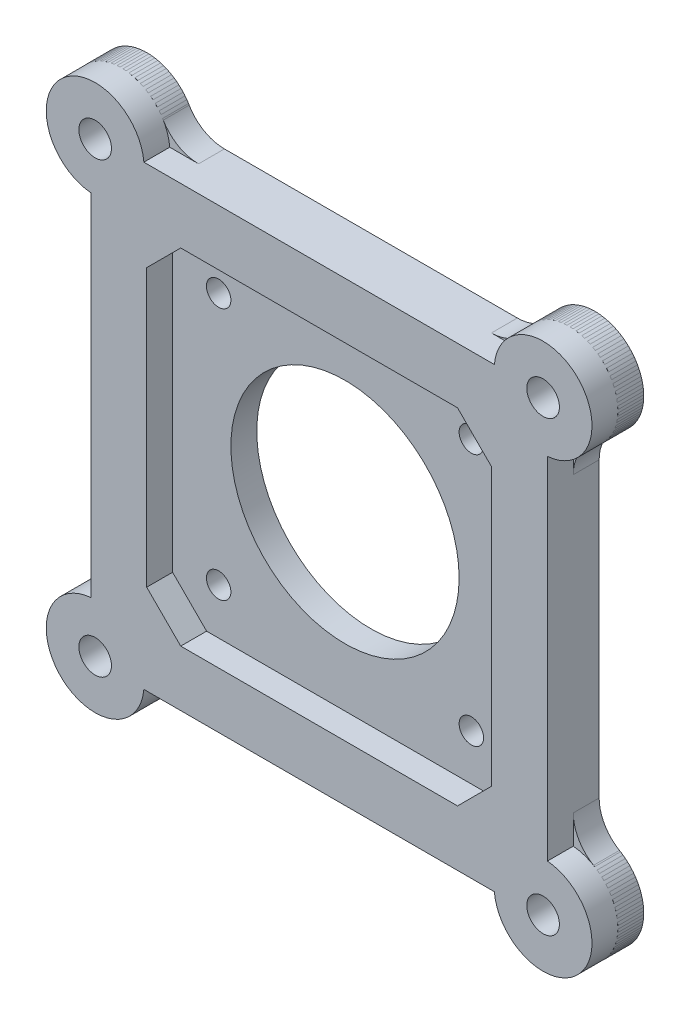
SolidWorks part; units mm, degrees
ref_plane "Plan de face" through (0, 0, 0) normal (0, 0, 1) x (1, 0, 0)
ref_plane "Plan de dessus" through (0, 0, 0) normal (0, 1, 0) x (1, 0, 0)
ref_plane "Plan de droite" through (0, 0, 0) normal (1, 0, 0) x (0, 0, -1)
sketch "Esquisse28" plane through (0, 0, 0) normal (0, 0, 1) x (1, 0, 0)
  line L0 (-21.5, -28.0054) -> (-28.0054, -21.5)
  line L1 (21.5, -28.0054) -> (-21.5, -28.0054)
  line L4 (28.0054, -21.5) -> (21.5, -28.0054)
  line L5 (28.0054, 21.5) -> (28.0054, -21.5)
  line L8 (21.5, 28.0054) -> (28.0054, 21.5)
  line L9 (-21.5, 28.0054) -> (21.5, 28.0054)
  line L10 (-28.0054, 21.5) -> (-21.5, 28.0054)
  line L11 (-28.0054, -21.5) -> (-28.0054, 21.5)
  line L16 (-16.9781, -21.15) -> (-21.15, -16.9781)
  line L17 (16.9781, -21.15) -> (-16.9781, -21.15)
  line L18 (21.15, -16.9781) -> (16.9781, -21.15)
  line L19 (21.15, 16.9781) -> (21.15, -16.9781)
  line L20 (16.9781, 21.15) -> (21.15, 16.9781)
  line L21 (-16.9781, 21.15) -> (16.9781, 21.15)
  line L22 (-21.15, 16.9781) -> (-16.9781, 21.15)
  line L23 (-21.15, -16.9781) -> (-21.15, 16.9781)
  point P1 (0, -21.15)
  point P2 (0, -28.0054)
  point P3 (28.0054, 0)
  point P24 (21.15, 0)
  dimension "D1" = 42.3
  dimension "D2" = 5.9
  dimension "D3" = 135
  dimension "D4" = 135
  dimension "D5" = 43
  dimension "D6" = 9.2
  dimension "D7" = 135
  dimension "D8" = 135
extrude "Boss.-Extru.2" add sketch "Esquisse28" along normal blind 6.35
sketch "Esquisse29" plane through (0, 0, 0) normal (0, 0, 1) x (1, 0, 0)
  line L0 (-46.0327, -46.0327) -> (46.0327, 46.0327) construction
  line L1 (-59.4617, 0) -> (59.4617, 0) construction
  circle A0 centre (27.4767, 27.4767) radius 6
  point P4 (0, 0)
  point P8 (0, 0)
  dimension "D2" = 12
  dimension "D1" = 45
extrude "Boss.-Extru.3" add sketch "Esquisse29" along normal up to surface (6.35 mm away) up to face at (0, 0, 6.35)
mirror "Symétrie1" about plane through (0, 0, 0) normal (1, 0, 0) of "Boss.-Extru.3"
mirror "Symétrie2" about plane through (0, 0, 0) normal (0, 1, 0) of "Symétrie1", "Boss.-Extru.3"
sketch "Esquisse30" plane through (0, 0, 6.35) normal (0, 0, 1) x (1, 0, 0)
  circle A0 centre (-27.4767, 27.4767) radius 2
  circle A1 centre (27.4767, 27.4767) radius 2
  circle A2 centre (27.4767, -27.4767) radius 2
  circle A3 centre (-27.4767, -27.4767) radius 2
  arc A4 (-28.0054, -21.5) -> (-21.5, -28.0054) centre (-27.4767, -27.4767) ccw construction
  arc A5 (-21.5, 28.0054) -> (-28.0054, 21.5) centre (-27.4767, 27.4767) ccw construction
  arc A6 (28.0054, 21.5) -> (21.5, 28.0054) centre (27.4767, 27.4767) ccw construction
  arc A7 (21.5, -28.0054) -> (28.0054, -21.5) centre (27.4767, -27.4767) ccw construction
  dimension "D1" = 4
extrude "Enlèv. mat.-Extru.1" cut sketch "Esquisse30" against normal through all
sketch "Esquisse31" plane through (0, 0, 0) normal (0, 0, 1) x (1, 0, 0)
  line L0 (-21.5, -28.0054) -> (21.5, -28.0054) construction
  line L1 (28.0054, -21.5) -> (28.0054, 21.5) construction
  line L2 (21.5, 28.0054) -> (-21.5, 28.0054) construction
  line L3 (-28.0054, 21.5) -> (-28.0054, -21.5) construction
  line L4 (-21.5, -28.0054) -> (21.5, -28.0054)
  line L5 (28.0054, -21.5) -> (28.0054, 21.5)
  line L6 (21.5, 28.0054) -> (-21.5, 28.0054)
  line L7 (-28.0054, 21.5) -> (-28.0054, -21.5)
  circle A0 centre (27.4767, 27.4767) radius 2 construction
  circle A1 centre (-27.4767, 27.4767) radius 2 construction
  circle A2 centre (-27.4767, -27.4767) radius 2 construction
  circle A3 centre (27.4767, -27.4767) radius 2 construction
  arc A4 (-28.0054, -21.5) -> (-21.5, -28.0054) centre (-27.4767, -27.4767) ccw construction
  arc A5 (21.5, -28.0054) -> (28.0054, -21.5) centre (27.4767, -27.4767) ccw construction
  arc A6 (28.0054, 21.5) -> (21.5, 28.0054) centre (27.4767, 27.4767) ccw construction
  arc A7 (-21.5, 28.0054) -> (-28.0054, 21.5) centre (-27.4767, 27.4767) ccw construction
  circle A8 centre (27.4767, 27.4767) radius 2
  circle A9 centre (-27.4767, 27.4767) radius 2
  circle A10 centre (-27.4767, -27.4767) radius 2
  circle A11 centre (27.4767, -27.4767) radius 2
  arc A12 (-28.0054, -21.5) -> (-21.5, -28.0054) centre (-27.4767, -27.4767) ccw
  arc A13 (21.5, -28.0054) -> (28.0054, -21.5) centre (27.4767, -27.4767) ccw
  arc A14 (28.0054, 21.5) -> (21.5, 28.0054) centre (27.4767, 27.4767) ccw
  arc A15 (-21.5, 28.0054) -> (-28.0054, 21.5) centre (-27.4767, 27.4767) ccw
extrude "Boss.-Extru.4" add sketch "Esquisse31" along normal blind 3.175 separate body
sketch "Esquisse32" plane through (0, 0, 3.175) normal (0, 0, 1) x (1, 0, 0)
  circle A0 centre (-15.5, -15.5) radius 1.5
  circle A1 centre (15.5, -15.5) radius 1.5
  circle A2 centre (15.5, 15.5) radius 1.5
  circle A3 centre (-15.5, 15.5) radius 1.5
  circle A4 centre (0, 0) radius 14
  dimension "D1" = 3
  dimension "D6" = 28
  dimension "D2" = 15.5
  dimension "D3" = 15.5
  dimension "D4" = 15.5
  dimension "D5" = 15.5
extrude "Enlèv. mat.-Extru.2" cut sketch "Esquisse32" against normal through all
fillet "Congé1" radius 5 8 edges at (-21.5, -28.0054, 1.5875) (-28.0054, -21.5, 1.5875) (28.0054, -21.5, 1.5875) (21.5, -28.0054, 1.5875) (21.5, 28.0054, 1.5875) (28.0054, 21.5, 1.5875) (-21.5, 28.0054, 1.5875) (-28.0054, 21.5, 1.5875)
